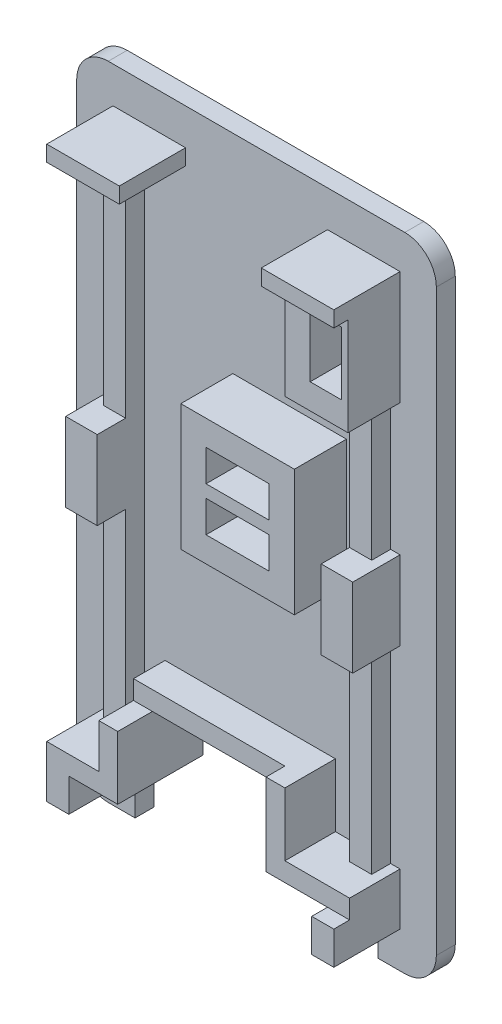
SolidWorks part; units mm, degrees
ref_plane "Plan de face" through (0, 0, 0) normal (0, 0, 1) x (1, 0, 0)
ref_plane "Plan de dessus" through (0, 0, 0) normal (0, 1, 0) x (1, 0, 0)
ref_plane "Plan de droite" through (0, 0, 0) normal (1, 0, 0) x (0, 0, -1)
sketch "Sketch1" plane through (0, 0, 0) normal (0, 0, 1) x (1, 0, 0)
  line L0 (-0.2, 36.5) -> (18.6, 36.5) construction
  line L1 (0, 0) -> (18.4, 0) construction
  line L2 (0, 0) -> (0, 36.3) construction
  line L3 (0, 36.3) -> (18.4, 36.3) construction
  line L4 (18.4, 0) -> (18.4, 36.3) construction
  line L5 (18.6, -0.2) -> (18.6, 36.5) construction
  line L6 (-0.2, -0.2) -> (18.6, -0.2) construction
  line L7 (-0.2, -0.2) -> (-0.2, 36.5) construction
  line L8 (-2.2, 38.5) -> (20.6, 38.5)
  line L9 (20.6, -2.2) -> (20.6, 38.5)
  line L10 (-2.2, -2.2) -> (20.6, -2.2)
  line L11 (-2.2, -2.2) -> (-2.2, 38.5)
  dimension "D1" = 36.3
  dimension "D2" = 18.4
  dimension "D3" = 0.2
  dimension "D4" = 2
extrude "Boss-Extrude1" add sketch "Sketch1" along normal blind 1.2
fillet "Fillet1" radius 2 4 edges at (-2.2, -2.2, 0.6) (20.6, -2.2, 0.6) (-2.2, 38.5, 0.6) (20.6, 38.5, 0.6)
sketch "Sketch4" plane through (0, 0, 1.2) normal (0, 0, 1) x (1, 0, 0)
  line L0 (9.2, -2.2) -> (9.2, 38.5) construction
  line L1 (-0.2, -2.2) -> (18.6, -2.2) construction
  line L2 (18.6, 38.5) -> (-0.2, 38.5) construction
  line L4 (1.5, 2.2) -> (16.9, 2.2)
  line L5 (1.5, 2.2) -> (1.5, -2.2)
  line L6 (1.5, -2.2) -> (16.9, -2.2)
  line L7 (16.9, 2.2) -> (16.9, -2.2)
  line L8 (1.5, 2.2) -> (16.9, -2.2) construction
  line L9 (1.5, -2.2) -> (16.9, 2.2) construction
  point P6 (9.2, 0)
  dimension "D1" = 15.4
  dimension "D2" = 4.4
extrude "Cut-Extrude1" cut sketch "Sketch4" against normal up to next and the other way through all
sketch "Sketch5" plane through (0, 0, 1.2) normal (0, 0, 1) x (1, 0, 0)
  line L1 (16.9, 2.2) -> (1.5, 2.2) construction
  line L2 (-0.2, -2.2) -> (1.5, -2.2) construction
  line L3 (4.6, 2.2) -> (13, 2.2)
  line L4 (4.6, 2.2) -> (4.6, 6.2)
  line L5 (4.6, 6.2) -> (13, 6.2)
  line L6 (13, 2.2) -> (13, 6.2)
  line L7 (4.6, 2.2) -> (13, 6.2) construction
  line L8 (4.6, 6.2) -> (13, 2.2) construction
  line L10 (20.6, -0.2) -> (20.6, 36.5) construction
  point P4 (8.8, 4.2)
  point P11 (0, 0)
  dimension "D1" = 8.4
  dimension "D2" = 8.4
  dimension "D3" = 16
extrude "Cut-Extrude2" cut sketch "Sketch5" against normal up to next
sketch "Sketch6" plane through (0, 0, 1.2) normal (0, 0, 1) x (1, 0, 0)
  line L0 (18.6, 38.5) -> (-0.2, 38.5) construction
  line L1 (-2.2, 38.5) -> (20.6, 38.5) construction
  line L2 (-2.2, 38.5) -> (-2.2, -2.2) construction
  line L3 (-2.2, -2.2) -> (20.6, -2.2) construction
  line L4 (20.6, 38.5) -> (20.6, -2.2) construction
  line L5 (-2.2, 36.5) -> (-2.2, -0.2) construction
  line L6 (20.6, -0.2) -> (20.6, 36.5) construction
  line L7 (-0.2, -2.2) -> (1.5, -2.2) construction
  line L8 (9.2, 38.5) -> (9.2, -2.2) construction
  line L9 (0.1, 36.2) -> (18.3, 36.2) construction
  line L10 (0, 0) -> (18.4, 0) construction
  line L11 (0, 0) -> (0, 36.3) construction
  line L12 (0, 36.3) -> (18.4, 36.3) construction
  line L13 (18.4, 0) -> (18.4, 36.3) construction
  line L14 (0, 0) -> (18.4, 36.3) construction
  line L15 (0, 36.3) -> (18.4, 0) construction
  line L16 (18.3, 0.1) -> (18.3, 36.2) construction
  line L17 (0.1, 0.1) -> (18.3, 0.1) construction
  line L18 (0.1, 0.1) -> (0.1, 36.2) construction
  line L19 (18.3, 35.2) -> (13.7, 35.2)
  line L20 (0.1, 36.2) -> (4.7, 36.2)
  line L21 (0.1, 36.2) -> (0.1, 35.2)
  line L22 (0.1, 35.2) -> (4.7, 35.2)
  line L23 (4.7, 36.2) -> (4.7, 35.2)
  line L24 (0.1, 0.1) -> (1.5, 0.1)
  line L25 (0.1, 0.1) -> (0.1, 2.2)
  line L26 (0.1, 2.2) -> (1.5, 2.2)
  line L27 (1.5, 0.1) -> (1.5, 2.2)
  line L28 (13.7, 36.2) -> (13.7, 35.2)
  line L29 (18.3, 36.2) -> (13.7, 36.2)
  line L30 (18.3, 36.2) -> (18.3, 35.2)
  line L31 (18.3, 2.2) -> (16.9, 2.2)
  line L32 (16.9, 0.1) -> (16.9, 2.2)
  line L33 (18.3, 0.1) -> (16.9, 0.1)
  line L34 (18.3, 0.1) -> (18.3, 2.2)
  point P16 (9.2, 18.15)
  point P31 (1.2, 2.2)
  point P40 (1.1324, 2.3635)
  dimension "D1" = 18.4
  dimension "D2" = 36.3
  dimension "D4" = 9
  dimension "D5" = 1
  dimension "D3" = 0.1
extrude "Boss-Extrude3" add sketch "Sketch6" along normal blind 4.2
sketch "Sketch7" plane through (0, 0, 1.2) normal (0, 0, 1) x (1, 0, 0)
  line L0 (4.6, 6.2) -> (4.6, 2.2) construction
  line L1 (0.1, 2.2) -> (4.6, 2.2)
  line L2 (0.1, 2.2) -> (0.1, 3.4)
  line L3 (0.1, 3.4) -> (4.6, 3.4)
  line L4 (4.6, 2.2) -> (4.6, 3.4)
  line L6 (3.4, 3.4) -> (4.6, 3.4)
  line L7 (3.4, 3.4) -> (3.4, 6.2)
  line L8 (3.4, 6.2) -> (4.6, 6.2)
  line L9 (4.6, 3.4) -> (4.6, 6.2)
  line M16 (0.1, 2.2) -> (1.5, 2.2)
  line M17 (1.5, 2.2) -> (4.6, 2.2)
  line M18 (4.6, 2.2) -> (4.6, 6.2)
  dimension "D1" = 1.2
extrude "Boss-Extrude4" add sketch "Sketch7" along normal up to surface (4.2 mm away) contours L3 L2 M16 M17 M18 | L8 L7 L3 M18 up to face at (0.8, 1.15, 5.4)
sketch "Sketch8" plane through (0, 0, 1.2) normal (0, 0, 1) x (1, 0, 0)
  line L0 (13, 2.2) -> (13, 6.2) construction
  line L1 (18.3, 2.2) -> (13, 2.2)
  line L2 (18.3, 2.2) -> (18.3, 3.4)
  line L3 (18.3, 3.4) -> (13, 3.4)
  line L4 (13, 2.2) -> (13, 3.4)
  line L6 (13, 3.4) -> (14.2, 3.4)
  line L7 (13, 3.4) -> (13, 7.4)
  line L8 (13, 7.4) -> (14.2, 7.4)
  line L9 (14.2, 3.4) -> (14.2, 7.4)
  line L10 (13, 7.4) -> (3.4, 7.4)
  line L11 (13, 7.4) -> (13, 6.2)
  line L12 (13, 6.2) -> (3.4, 6.2)
  line L13 (3.4, 7.4) -> (3.4, 6.2)
  line M13 (3.4, 6.2) -> (4.6, 6.2)
  line M14 (4.6, 6.2) -> (13, 6.2)
  line M15 (13, 6.2) -> (13, 2.2)
  line M16 (13, 2.2) -> (16.9, 2.2)
  line M17 (16.9, 2.2) -> (18.3, 2.2)
  dimension "D1" = 1.2
extrude "Boss-Extrude5" add sketch "Sketch8" along normal offset from surface (2 mm away) 2.2 contours L10 L13 L7 M13 M14 | L3 L9 L8 L7 M15 | L2 L3 M15 M16 M17 up to face at (2.4, 2.975, 5.4)
sketch "Sketch9" plane through (0, 0, 3.2) normal (0, 0, 1) x (1, 0, 0)
  line L0 (13, 6.2) -> (13, 7.4)
  line L10 (3.4, 7.4) -> (3.4, 6.2)
  line L11 (3.4, 6.2) -> (4.6, 6.2)
  line L12 (4.6, 6.2) -> (13, 6.2)
  line L13 (13, 6.2) -> (13, 2.2)
  line L14 (13, 2.2) -> (16.9, 2.2)
  line L15 (16.9, 2.2) -> (18.3, 2.2)
  line L16 (18.3, 2.2) -> (18.3, 3.4)
  line L17 (18.3, 3.4) -> (14.2, 3.4)
  line L18 (14.2, 3.4) -> (14.2, 7.4)
  line L19 (14.2, 7.4) -> (3.4, 7.4)
  line L20 (3.4, 7.4) -> (3.4, 6.2)
  line L21 (3.4, 6.2) -> (4.6, 6.2)
  line L22 (4.6, 6.2) -> (13, 6.2)
  line L23 (13, 6.2) -> (13, 2.2)
  line L24 (13, 2.2) -> (16.9, 2.2)
  line L25 (16.9, 2.2) -> (18.3, 2.2)
  line L26 (18.3, 2.2) -> (18.3, 3.4)
  line L27 (18.3, 3.4) -> (14.2, 3.4)
  line L28 (14.2, 3.4) -> (14.2, 7.4)
  line L29 (14.2, 7.4) -> (3.4, 7.4)
  line M14 (13, 6.2) -> (13, 2.2)
  line M15 (13, 2.2) -> (16.9, 2.2)
  line M16 (16.9, 2.2) -> (18.3, 2.2)
  line M17 (18.3, 2.2) -> (18.3, 3.4)
  line M18 (18.3, 3.4) -> (14.2, 3.4)
  line M19 (14.2, 3.4) -> (14.2, 7.4)
  line M20 (14.2, 7.4) -> (3.4, 7.4)
  dimension "D1" = 0
extrude "Boss-Extrude6" add sketch "Sketch9" along normal offset from surface (1.2 mm away) 1 contours L0 M14 M15 M16 M17 M18 M19 M20 up to face at (17.6, 1.15, 5.4)
sketch "Sketch10" plane through (0, 0, 1.2) normal (0, 0, 1) x (1, 0, 0)
  line L1 (15.9, 30.6) -> (17.9, 30.6)
  line L2 (15.9, 30.6) -> (15.9, 34.6)
  line L3 (15.9, 34.6) -> (17.9, 34.6)
  line L4 (17.9, 30.6) -> (17.9, 34.6)
  line L5 (15.9, 30.6) -> (17.9, 34.6) construction
  line L6 (15.9, 34.6) -> (17.9, 30.6) construction
  line L7 (18.3, 0.1) -> (18.3, 36.2) construction
  line L8 (18.3, 36.2) -> (13.7, 36.2) construction
  line L9 (11.3, 22.7) -> (11.3, 19.9) construction
  line L10 (9.3, 21.7) -> (13.3, 21.7)
  line L11 (9.3, 21.7) -> (9.3, 23.7)
  line L12 (9.3, 23.7) -> (13.3, 23.7)
  line L13 (13.3, 21.7) -> (13.3, 23.7)
  line L14 (9.3, 21.7) -> (13.3, 23.7) construction
  line L15 (9.3, 23.7) -> (13.3, 21.7) construction
  line L17 (13.3, 18.9) -> (9.3, 18.9)
  line L18 (13.3, 18.9) -> (13.3, 20.9)
  line L19 (13.3, 20.9) -> (9.3, 20.9)
  line L20 (9.3, 18.9) -> (9.3, 20.9)
  line L21 (13.3, 18.9) -> (9.3, 20.9) construction
  line L22 (13.3, 20.9) -> (9.3, 18.9) construction
  line L24 (0.1, 36.2) -> (18.3, 36.2) construction
  point P0 (16.9, 32.6)
  point P9 (11.3, 22.7)
  point P20 (11.3, 21.3)
  dimension "D1" = 1.4
  dimension "D2" = 2
  dimension "D3" = 4
  dimension "D4" = 3.6
  dimension "D5" = 7
  dimension "D6" = 2.8
  dimension "D7" = 14.9
extrude "Cut-Extrude3" cut sketch "Sketch10" against normal offset from surface (0.8 mm away) 0.4 up to face at (9.1, 10.125, 0)
sketch "Sketch11" plane through (0, 0, 1.2) normal (0, 0, 1) x (1, 0, 0)
  line L0 (17.9, 30.6) -> (17.9, 34.6) construction
  line L1 (17.9, 34.6) -> (15.9, 34.6) construction
  line L2 (15.9, 34.6) -> (15.9, 30.6) construction
  line L3 (15.9, 30.6) -> (17.9, 30.6) construction
  line L4 (9.3, 20.9) -> (9.3, 18.9) construction
  line L5 (9.3, 18.9) -> (13.3, 18.9) construction
  line L6 (13.3, 18.9) -> (13.3, 20.9) construction
  line L7 (13.3, 20.9) -> (9.3, 20.9) construction
  line L8 (13.3, 21.7) -> (13.3, 23.7) construction
  line L9 (13.3, 23.7) -> (9.3, 23.7) construction
  line L10 (9.3, 23.7) -> (9.3, 21.7) construction
  line L11 (9.3, 21.7) -> (13.3, 21.7) construction
  line L12 (17.9, 30.6) -> (17.9, 34.6)
  line L13 (17.9, 34.6) -> (15.9, 34.6)
  line L14 (15.9, 34.6) -> (15.9, 30.6)
  line L15 (15.9, 30.6) -> (17.9, 30.6)
  line L16 (9.3, 20.9) -> (9.3, 18.9)
  line L17 (9.3, 18.9) -> (13.3, 18.9)
  line L18 (13.3, 18.9) -> (13.3, 20.9)
  line L19 (13.3, 20.9) -> (9.3, 20.9)
  line L20 (13.3, 21.7) -> (13.3, 23.7)
  line L21 (13.3, 23.7) -> (9.3, 23.7)
  line L22 (9.3, 23.7) -> (9.3, 21.7)
  line L23 (9.3, 21.7) -> (13.3, 21.7)
  line L24 (11.3, 21.7) -> (11.3, 20.9) construction
  line L26 (14.9, 17.3) -> (7.7, 17.3)
  line L27 (14.9, 17.3) -> (14.9, 25.3)
  line L28 (14.9, 25.3) -> (7.7, 25.3)
  line L29 (7.7, 17.3) -> (7.7, 25.3)
  line L30 (14.9, 17.3) -> (7.7, 25.3) construction
  line L31 (14.9, 25.3) -> (7.7, 17.3) construction
  line L32 (18.3, 35.2) -> (14.3, 35.2)
  line L33 (18.3, 35.2) -> (18.3, 29)
  line L34 (18.3, 29) -> (14.3, 29)
  line L35 (14.3, 35.2) -> (14.3, 29)
  point P6 (11.3, 21.3)
  dimension "D1" = 1.6
  dimension "D2" = 1.6
  dimension "D3" = 1.6
  dimension "D4" = 1.6
extrude "Boss-Extrude7" add sketch "Sketch11" along normal offset from surface (3.3 mm away) 0.9 up to face at (2.4, 2.975, 5.4)
sketch "Sketch12" plane through (0, 0, 1.2) normal (0, 0, 1) x (1, 0, 0)
  line L0 (9.2, 18.15) -> (0.1, 18.15) construction
  line L1 (0.1, 0.1) -> (0.1, 36.2) construction
  line L2 (9.2, 38.5) -> (9.2, -2.2) construction
  line L3 (2.1, 15.65) -> (0.1, 15.65)
  line L4 (2.1, 15.65) -> (2.1, 20.65)
  line L5 (2.1, 20.65) -> (0.1, 20.65)
  line L6 (0.1, 15.65) -> (0.1, 20.65)
  line L7 (2.1, 15.65) -> (0.1, 20.65) construction
  line L8 (2.1, 20.65) -> (0.1, 15.65) construction
  line L9 (9.2, 38.5) -> (9.2, -2.2) construction
  line L10 (16.3, 20.65) -> (18.3, 20.65)
  line L11 (18.3, 15.65) -> (18.3, 20.65)
  line L12 (16.3, 15.65) -> (18.3, 15.65)
  line L13 (16.3, 15.65) -> (16.3, 20.65)
  point P5 (1.1, 18.15)
  dimension "D1" = 2
  dimension "D2" = 5
extrude "Boss-Extrude8" add sketch "Sketch12" along normal blind 3
sketch "Sketch13" plane through (0, 0, 1.2) normal (0, 0, 1) x (1, 0, 0)
  line L0 (0.1, 35.2) -> (4.7, 35.2) construction
  line L1 (2.1, 20.65) -> (0.7, 20.65)
  line L2 (2.1, 20.65) -> (2.1, 35.2)
  line L3 (2.1, 35.2) -> (0.7, 35.2)
  line L4 (0.7, 20.65) -> (0.7, 35.2)
  line L5 (14.3, 29) -> (18.3, 29) construction
  line L6 (16.3, 20.65) -> (17.7, 20.65)
  line L7 (16.3, 20.65) -> (16.3, 29)
  line L8 (16.3, 29) -> (17.7, 29)
  line L9 (17.7, 20.65) -> (17.7, 29)
  line L10 (18.3, 3.4) -> (14.2, 3.4) construction
  line L11 (16.3, 15.65) -> (17.7, 15.65)
  line L12 (16.3, 15.65) -> (16.3, 3.4)
  line L13 (16.3, 3.4) -> (17.7, 3.4)
  line L14 (17.7, 15.65) -> (17.7, 3.4)
  line L15 (3.4, 3.4) -> (0.1, 3.4) construction
  line L16 (2.1, 15.65) -> (0.7, 15.65)
  line L17 (2.1, 15.65) -> (2.1, 3.4)
  line L18 (2.1, 3.4) -> (0.7, 3.4)
  line L19 (0.7, 15.65) -> (0.7, 3.4)
  dimension "D1" = 1.4
extrude "Boss-Extrude9" add sketch "Sketch13" along normal offset from surface (1.2 mm away) 3 up to face at (2.4, 2.975, 5.4)
